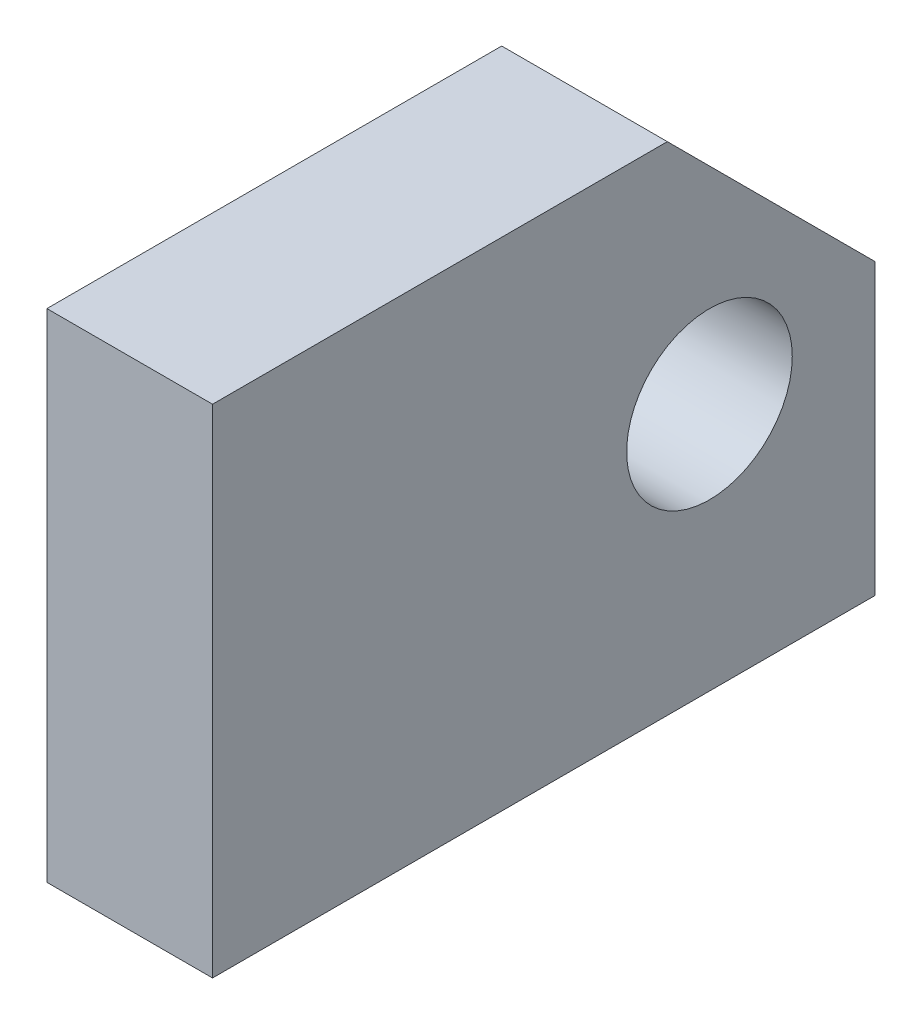
SolidWorks part; units mm, degrees
ref_plane "Płaszczyzna przednia" through (0, 0, 0) normal (0, 0, 1) x (1, 0, 0)
ref_plane "Płaszczyzna górna" through (0, 0, 0) normal (0, 1, 0) x (1, 0, 0)
ref_plane "Płaszczyzna prawa" through (0, 0, 0) normal (1, 0, 0) x (0, 0, -1)
sketch "Szkic1" plane through (0, 0, 0) normal (1, 0, 0) x (0, 0, -1)
  line L0 (7.4567, 15) -> (20, 2.4567)
  line L1 (-20, -15) -> (20, -15)
  line L2 (-20, -15) -> (-20, 15)
  line L3 (-20, 15) -> (7.4567, 15)
  line L4 (20, -15) -> (20, 2.4567)
  line L5 (-20, -15) -> (12.8324, 9.6243) construction
  line L6 (-20, 15) -> (20, -15) construction
  circle A0 centre (10, 0) radius 5
  point P0 (0, 0)
  dimension "D1" = 10
  dimension "D7" = 10
  dimension "D2" = 40
  dimension "D3" = 30
  dimension "D4" = 27.4567
  dimension "D5" = 17.4567
  dimension "D6" = 20
  dimension "D8" = 15
extrude "Dodanie-wyciągnięcie1" add sketch "Szkic1" along normal blind 10
